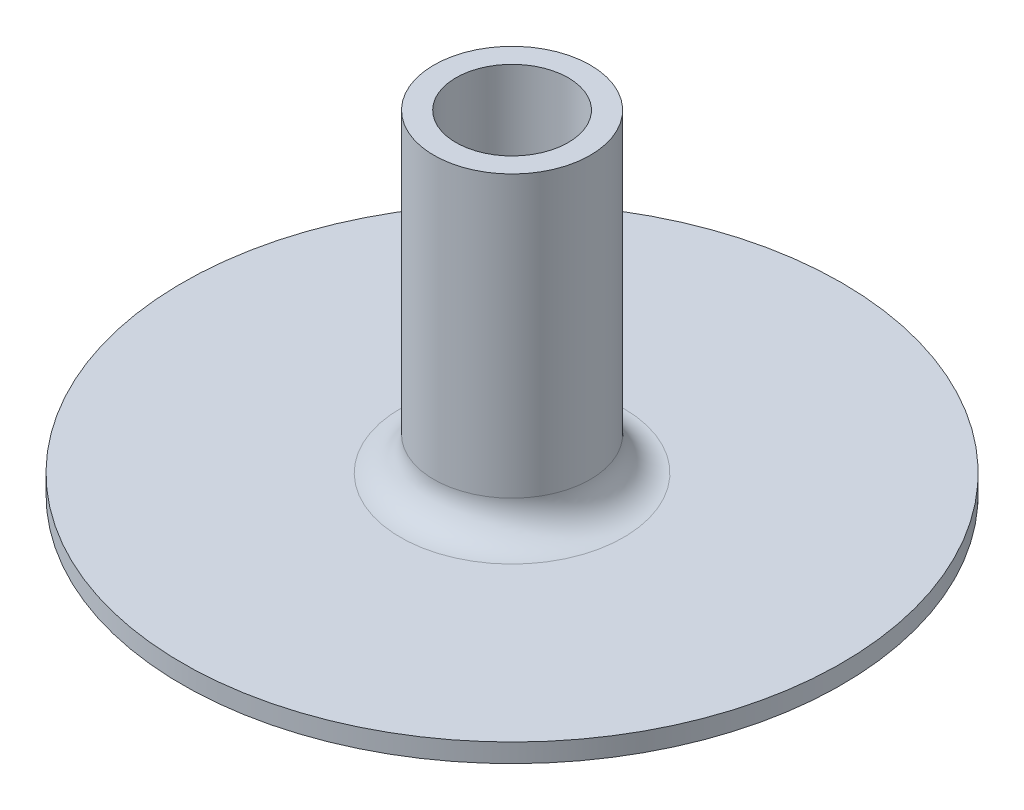
SolidWorks part; units mm, degrees
material "Brass"
ref_plane "Front Plane" through (0, 0, 0) normal (0, 0, 1) x (1, 0, 0)
ref_plane "Top Plane" through (0, 0, 0) normal (0, 1, 0) x (1, 0, 0)
ref_plane "Right Plane" through (0, 0, 0) normal (1, 0, 0) x (0, 0, -1)
sketch "Sketch1" plane through (0, 0, 0) normal (0, 0, 1) x (1, 0, 0)
  line L0 (0, 0) -> (0, 85.2107) construction
  line L1 (-1.0668, 0) -> (-1.0668, 6.3246)
  line L2 (-1.0668, 6.3246) -> (-1.4859, 6.3246)
  line L3 (-1.4859, 6.3246) -> (-1.4859, 0.3556)
  line L4 (-1.4859, 0.3556) -> (-6.2611, 0.3556)
  line L5 (-6.2611, 0.3556) -> (-6.2611, 0)
  line L6 (-6.2611, 0) -> (-1.0668, 0)
  dimension "D1" = 2.1336
  dimension "D2" = 0.3556
  dimension "D3" = 2.9718
  dimension "D4" = 12.5222
  dimension "D5" = 6.3246
revolve "Revolve1" add sketch "Sketch1" angle 360 about L0
fillet "Fillet1" radius 0.635 2 edges at (0, 0, -1.0668) (0, 0.3556, -1.4859)
